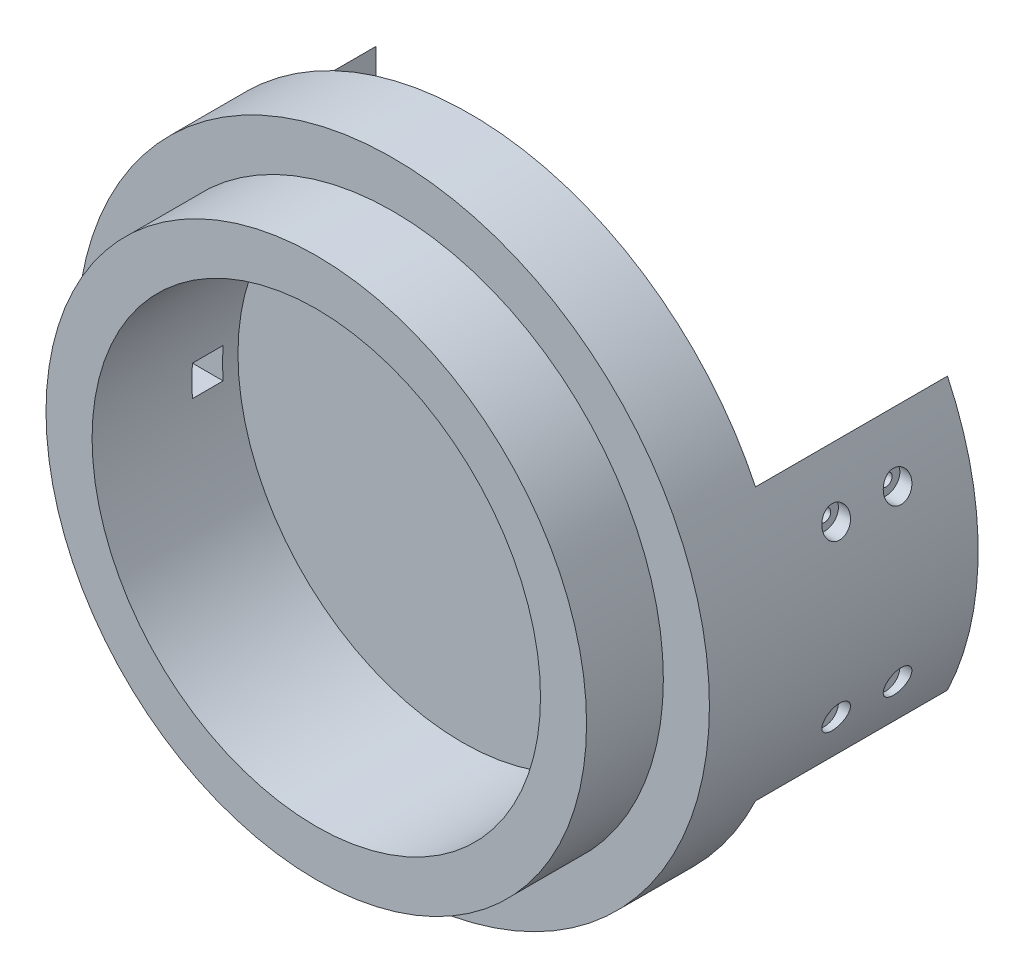
SolidWorks part; units mm, degrees
ref_plane "前视基准面" through (0, 0, 0) normal (0, 0, 1) x (1, 0, 0)
ref_plane "上视基准面" through (0, 0, 0) normal (0, 1, 0) x (1, 0, 0)
ref_plane "右视基准面" through (0, 0, 0) normal (1, 0, 0) x (0, 0, -1)
sketch "草图1" plane through (0, 0, 0) normal (0, 0, 1) x (1, 0, 0)
  circle A0 centre (0, 0) radius 41.2
extrude "凸台-拉伸1" add sketch "草图1" along normal blind 20
sketch "草图2" plane through (0, 0, 20) normal (0, 0, 1) x (1, 0, 0)
  circle A0 centre (0, 0) radius 29.2
extrude "切除-拉伸1" cut sketch "草图2" against normal blind 10
sketch "草图3" plane through (0, 0, 20) normal (0, 0, 1) x (1, 0, 0)
  circle A0 centre (0, 0) radius 35.2
extrude "切除-拉伸2" cut sketch "草图3" against normal blind 10 flip side to cut
sketch "草图4" plane through (0, 0, 10) normal (0, 0, 1) x (1, 0, 0)
  circle A0 centre (0, 0) radius 29.2
extrude "切除-拉伸3" cut sketch "草图4" against normal blind 9
sketch "草图5" plane through (0, 0, 0) normal (0, 0, -1) x (-1, 0, 0)
  line L0 (35.2, 2) -> (35.2, -2)
  line L1 (35.2, 2) -> (38.2, 2)
  line L2 (35.2, -2) -> (38.2, -2)
  line L3 (38.2, 2) -> (38.2, -2)
extrude "切除-拉伸4" cut sketch "草图5" against normal blind 7
sketch "草图6" plane through (-35.2, 0, 0) normal (-1, 0, 0) x (0, 0, 1)
  line L0 (3, 2) -> (3, -2)
  line L1 (3, 2) -> (7, 2)
  line L2 (3, -2) -> (7, -2)
  line L3 (7, 2) -> (7, -2)
extrude "切除-拉伸5" cut sketch "草图6" against normal blind 7
sketch "草图7" plane through (0, 0, 0) normal (0, 0, -1) x (-1, 0, 0)
  line L0 (37.2, 41.2) -> (37.2, -41.2)
  line L1 (37.2, 41.2) -> (41.2, 41.2)
  line L2 (37.2, -41.2) -> (41.2, -41.2)
  line L3 (41.2, 41.2) -> (41.2, -41.2)
  line L4 (-37.2, 41.2) -> (-37.2, -41.2)
  line L5 (-37.2, 41.2) -> (-41.2, 41.2)
  line L6 (-37.2, -41.2) -> (-41.2, -41.2)
  line L7 (-41.2, 41.2) -> (-41.2, -41.2)
extrude "凸台-拉伸2" add sketch "草图7" along normal blind 25
sketch "草图8" plane through (0, 0, 0) normal (0, 0, -1) x (-1, 0, 0)
  circle A0 centre (0, 0) radius 41.2
extrude "切除-拉伸6" cut sketch "草图8" along normal blind 25 flip side to cut
sketch "草图9" plane through (0, 0, 0) normal (0, 0, -1) x (-1, 0, 0)
  line L0 (35.2, 2) -> (35.2, -2)
  line L1 (35.2, 2) -> (38.2, 2)
  line L2 (35.2, -2) -> (38.2, -2)
  line L3 (38.2, 2) -> (38.2, -2)
extrude "切除-拉伸7" cut sketch "草图9" along normal blind 25
sketch "草图10" plane through (0, 0, 0) normal (0, 0, -1) x (-1, 0, 0)
  circle A0 centre (34.7, 11) radius 2
  circle A1 centre (34.7, -11) radius 2
  circle A2 centre (-34.7, 11) radius 2
  circle A3 centre (-34.7, -11) radius 2
extrude "切除-拉伸8" cut sketch "草图10" against normal blind 9
sketch "草图11" plane through (37.2, 0, 0) normal (-1, 0, 0) x (0, 0, 1)
  circle A0 centre (-16, -11) radius 0.8
  circle A1 centre (-8, -11) radius 0.8
  circle A2 centre (-16, 11) radius 0.8
  circle A3 centre (-8, 11) radius 0.8
extrude "切除-拉伸9" cut sketch "草图11" against normal blind 1
sketch "草图12" plane through (38.2, 0, 0) normal (-1, 0, 0) x (0, 0, 1)
  circle A0 centre (-16, -11) radius 1.8
  circle A1 centre (-8, -11) radius 1.8
  circle A2 centre (-16, 11) radius 1.8
  circle A3 centre (-8, 11) radius 1.8
extrude "切除-拉伸13" cut sketch "草图12" against normal blind 3
sketch "草图13" plane through (-37.2, 0, 0) normal (1, 0, 0) x (0, 0, -1)
  circle A0 centre (8, 11) radius 0.8
  circle A1 centre (16, 11) radius 0.8
  circle A2 centre (8, -11) radius 0.8
  circle A3 centre (16, -11) radius 0.8
extrude "切除-拉伸14" cut sketch "草图13" against normal blind 1
sketch "草图14" plane through (-38.2, 0, 0) normal (1, 0, 0) x (0, 0, -1)
  circle A0 centre (8, 11) radius 1.8
  circle A1 centre (16, 11) radius 1.8
  circle A2 centre (8, -11) radius 1.8
  circle A3 centre (16, -11) radius 1.8
extrude "切除-拉伸15" cut sketch "草图14" against normal blind 3
sketch "草图15" plane through (0, 0, 20) normal (0, 0, 1) x (1, 0, 0)
  line L0 (0, 41.2) -> (0, -41.2)
  circle A0 centre (0, 0) radius 41.2 construction
